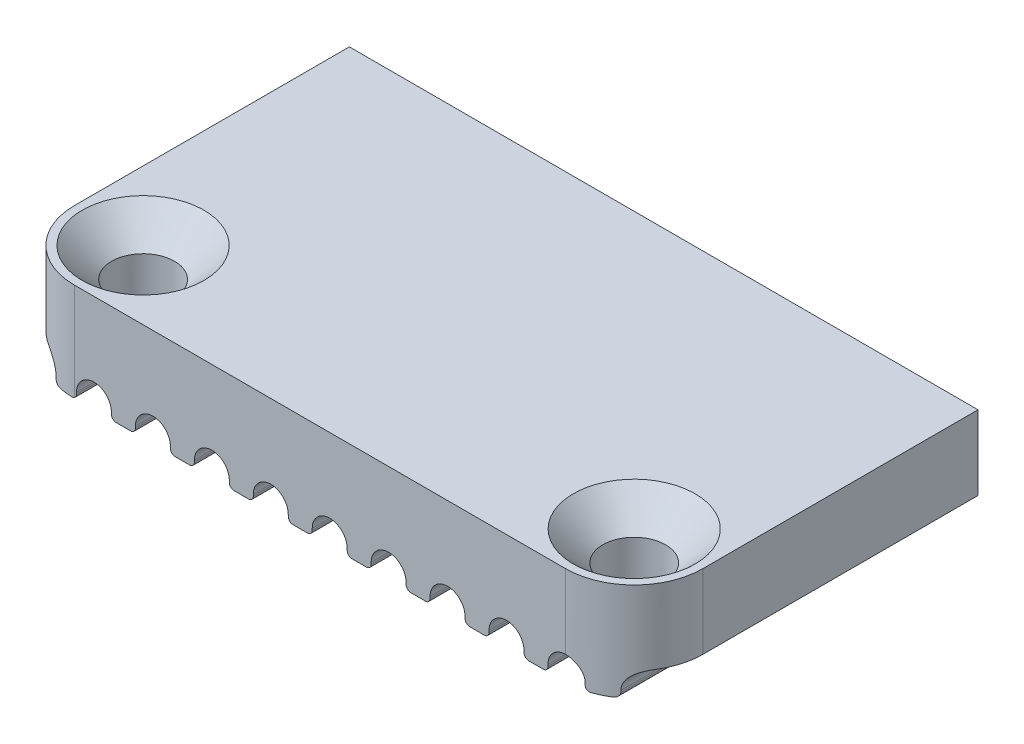
SolidWorks part; units mm, degrees
ref_plane "前视基准面" through (0, 0, 0) normal (0, 0, 1) x (1, 0, 0)
ref_plane "上视基准面" through (0, 0, 0) normal (0, 1, 0) x (1, 0, 0)
ref_plane "右视基准面" through (0, 0, 0) normal (1, 0, 0) x (0, 0, -1)
sketch "草图1" plane through (0, 0, 0) normal (0, 0, 1) x (1, 0, 0)
  line L1 (16, -2.5) -> (-16, -2.5)
  line L2 (16, -2.5) -> (16, 2.5)
  line L3 (16, 2.5) -> (-16, 2.5)
  line L4 (-16, -2.5) -> (-16, 2.5)
  line L5 (16, -2.5) -> (-16, 2.5) construction
  line L6 (16, 2.5) -> (-16, -2.5) construction
  point P0 (0, 0)
  dimension "D1" = 5
  dimension "D2" = 32
extrude "凸台-拉伸1" add sketch "草图1" along normal mid plane 17.5
sketch "草图2" plane through (0, 0, 8.75) normal (0, 0, 1) x (1, 0, 0)
  line L1 (-16, -2.5) -> (-15.63, -2.5)
  line L2 (-16, -2.5) -> (16, -2.5) construction
  line L3 (-15.39, -2.26) -> (-15.39, -2.17)
  line L4 (-13.61, -2.17) -> (-13.61, -2.26)
  line L5 (-13.37, -2.5) -> (-13, -2.5)
  line L6 (-16, -2.5) -> (-16, -3.5)
  line L7 (-16, -3.5) -> (-13, -3.5)
  line L8 (-13, -3.5) -> (-13, -2.5)
  arc A0 (-15.39, -2.17) -> (-13.61, -2.17) centre (-14.5, -2.17) cw
  arc A1 (-13.61, -2.26) -> (-13.37, -2.5) centre (-13.37, -2.26) ccw
  arc A2 (-15.63, -2.5) -> (-15.39, -2.26) centre (-15.63, -2.26) ccw
  point P13 (-15.39, -2.215)
  point P14 (-14.5, -1.28)
  point P17 (-13.61, -2.5)
  point P20 (-15.39, -2.5)
  dimension "D1" = 3
  dimension "D4" = 1.22
  dimension "D5" = 0.24
  dimension "D2" = 1
  dimension "D3" = 1.78
extrude "切除-拉伸1" cut sketch "草图2" against normal through all
pattern_linear "阵列(线性)1" count 11 spacing 3 along (1, 0, 0) of "切除-拉伸1"
sketch "草图3" plane through (0, 0, 8.75) normal (0, 0, 1) x (1, 0, 0)
  line L0 (-14.5, -1.28) -> (-16, -1.28)
  line L2 (-16, -1.28) -> (-16, -2.5)
  line L3 (-16, -2.5) -> (-14.5, -2.5)
  line L4 (-14.5, -2.5) -> (-14.5, -1.28)
  line L5 (15.5, -1.28) -> (16, -1.28)
  line L6 (16, -1.4337) -> (16, 2.5) construction
  line L7 (16, -1.28) -> (16, -2.5)
  line L8 (16, -2.5) -> (15.5, -2.5)
  line L9 (15.5, -2.5) -> (15.5, -1.28)
  line L10 (-16, 2.5) -> (-16, -2.5) construction
  arc A0 (-13.61, -2.17) -> (-15.39, -2.17) centre (-14.5, -2.17) ccw construction
  arc A1 (16, -1.4337) -> (14.61, -2.17) centre (15.5, -2.17) ccw construction
extrude "切除-拉伸2" cut sketch "草图3" against normal through all
sketch "草图4" plane through (0, 2.5, 0) normal (0, 1, 0) x (1, 0, 0)
  line L0 (-12.5, -5.25) -> (12.5, -5.25) construction
  line L1 (16, -8.75) -> (-16, -8.75) construction
  line L2 (-16, -8.75) -> (-16, 8.75) construction
  circle A0 centre (-12.5, -5.25) radius 1.6
  circle A1 centre (12.5, -5.25) radius 1.6
  point P4 (0, -5.25)
  dimension "D1" = 3.5
  dimension "D2" = 3.5
  dimension "D3" = 3.2
extrude "切除-拉伸3" cut sketch "草图4" against normal through all
chamfer "倒角1" distance 1.5 angle 45 2 edges at (10.9, 2.5, 5.25) (-14.1, 2.5, 5.25)
fillet "圆角1" radius 3.5 2 edges at (-16, 0.61, 8.75) (16, 0.61, 8.75)
